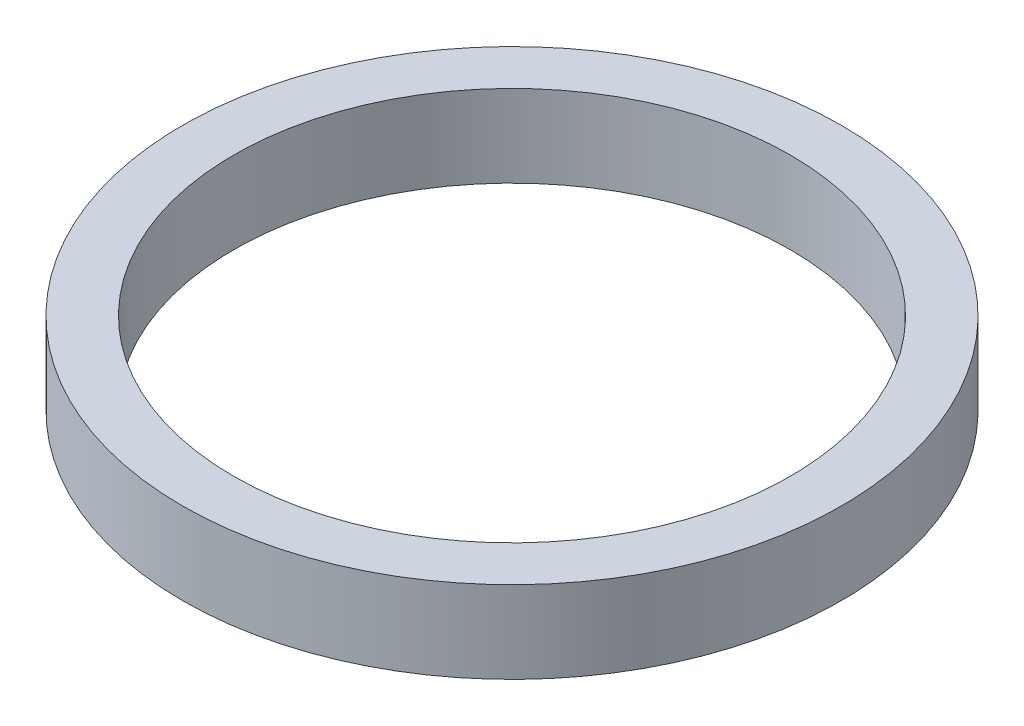
SolidWorks part; units mm, degrees
ref_plane "Alzado" through (0, 0, 0) normal (0, 0, 1) x (1, 0, 0)
ref_plane "Planta" through (0, 0, 0) normal (0, 1, 0) x (1, 0, 0)
ref_plane "Vista lateral" through (0, 0, 0) normal (1, 0, 0) x (0, 0, -1)
sketch "Croquis1" plane through (0, 0, 0) normal (0, 0, 1) x (1, 0, 0)
  line L0 (-19, 0) -> (-19, 5.6)
  line L1 (-19, 5.6) -> (-22.5, 5.6)
  line L2 (-22.5, 5.6) -> (-22.5, 0)
  line L3 (-22.5, 0) -> (-19, 0)
  line L4 (0, -6.6744) -> (0, 9.5116) construction
  dimension "D1" = 5.6
  dimension "D2" = 3.5
  dimension "D3" = 19
revolve "Revolución1" add sketch "Croquis1" angle 360 about L4
